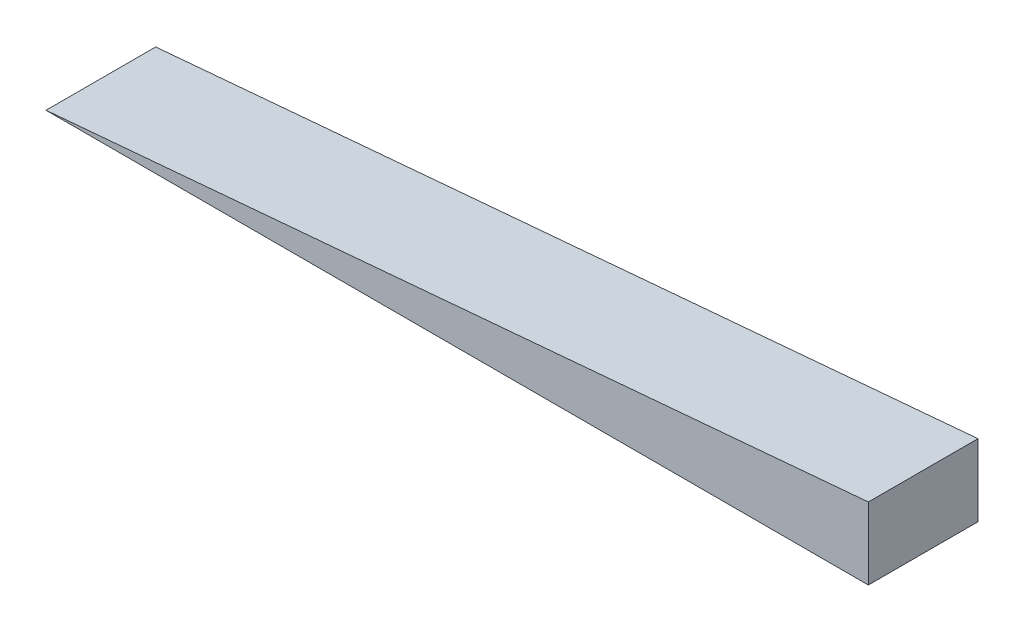
SolidWorks part; units mm, degrees
ref_plane "Front Plane" through (0, 0, 0) normal (0, 0, 1) x (1, 0, 0)
ref_plane "Top Plane" through (0, 0, 0) normal (0, 1, 0) x (1, 0, 0)
ref_plane "Right Plane" through (0, 0, 0) normal (1, 0, 0) x (0, 0, -1)
sketch "Sketch1" plane through (0, 0, 0) normal (0, 0, 1) x (1, 0, 0)
  line L0 (-104.4564, 0) -> (45.5436, 0)
  line L1 (55, 0) -> (-55, 0) construction
  line L2 (45.5436, 0) -> (45.5436, 13.1233)
  line L3 (45.5436, 13.1233) -> (-104.4564, 0)
  dimension "D1" = 150
  dimension "D2" = 5
extrude "Boss-Extrude1" add sketch "Sketch1" along normal mid plane 20
